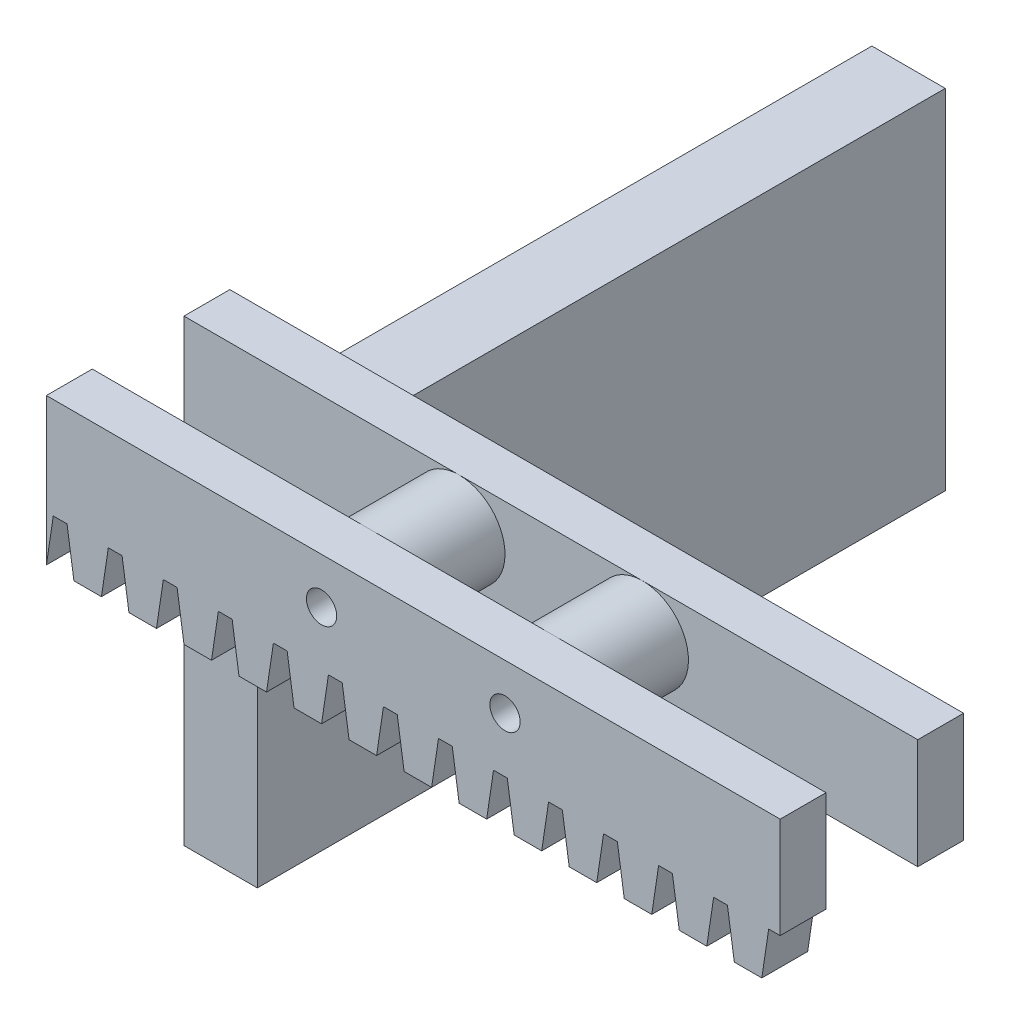
SolidWorks part; units mm, degrees
material "ABS"
ref_plane "正面" through (0, 0, 0) normal (0, 0, 1) x (1, 0, 0)
ref_plane "平面" through (0, 0, 0) normal (0, 1, 0) x (1, 0, 0)
ref_plane "右側面" through (0, 0, 0) normal (1, 0, 0) x (0, 0, -1)
sketch "ｽｹｯﾁ1" plane through (0, 0, 0) normal (0, 0, 1) x (1, 0, 0)
  line L1 (0, 0) -> (80, 0)
  line L2 (0, 0) -> (0, 16)
  line L3 (0, 16) -> (80, 16)
  line L4 (80, 0) -> (80, 16)
  dimension "D1" = 16
  dimension "D2" = 80
extrude "ﾎﾞｽ - 押し出し1" add sketch "ｽｹｯﾁ1" along normal blind 5
sketch "ｽｹｯﾁ2" plane through (0, 0, 5) normal (0, 0, 1) x (1, 0, 0)
  line L0 (0, 0) -> (0.75, 5)
  line L1 (0.75, 5) -> (2.25, 5)
  line L2 (2.25, 5) -> (3, 0)
  line L3 (0, 0) -> (80, 0) construction
  line L4 (0, 0) -> (3, 0)
  line L5 (6, 0) -> (9, 0)
  line L6 (8.25, 5) -> (9, 0)
  line L7 (6.75, 5) -> (8.25, 5)
  line L8 (6, 0) -> (6.75, 5)
  line L9 (12, 0) -> (15, 0)
  line L10 (14.25, 5) -> (15, 0)
  line L11 (12.75, 5) -> (14.25, 5)
  line L12 (12, 0) -> (12.75, 5)
  line L13 (18, 0) -> (21, 0)
  line L14 (20.25, 5) -> (21, 0)
  line L15 (18.75, 5) -> (20.25, 5)
  line L16 (18, 0) -> (18.75, 5)
  line L17 (24, 0) -> (27, 0)
  line L18 (26.25, 5) -> (27, 0)
  line L19 (24.75, 5) -> (26.25, 5)
  line L20 (24, 0) -> (24.75, 5)
  line L21 (30, 0) -> (33, 0)
  line L22 (32.25, 5) -> (33, 0)
  line L23 (30.75, 5) -> (32.25, 5)
  line L24 (30, 0) -> (30.75, 5)
  line L25 (36, 0) -> (39, 0)
  line L26 (38.25, 5) -> (39, 0)
  line L27 (36.75, 5) -> (38.25, 5)
  line L28 (36, 0) -> (36.75, 5)
  line L29 (42, 0) -> (45, 0)
  line L30 (44.25, 5) -> (45, 0)
  line L31 (42.75, 5) -> (44.25, 5)
  line L32 (42, 0) -> (42.75, 5)
  line L33 (48, 0) -> (51, 0)
  line L34 (50.25, 5) -> (51, 0)
  line L35 (48.75, 5) -> (50.25, 5)
  line L36 (48, 0) -> (48.75, 5)
  line L37 (54, 0) -> (57, 0)
  line L38 (56.25, 5) -> (57, 0)
  line L39 (54.75, 5) -> (56.25, 5)
  line L40 (54, 0) -> (54.75, 5)
  line L41 (60, 0) -> (63, 0)
  line L42 (62.25, 5) -> (63, 0)
  line L43 (60.75, 5) -> (62.25, 5)
  line L44 (60, 0) -> (60.75, 5)
  line L45 (66, 0) -> (69, 0)
  line L46 (68.25, 5) -> (69, 0)
  line L47 (66.75, 5) -> (68.25, 5)
  line L48 (66, 0) -> (66.75, 5)
  line L49 (72, 0) -> (75, 0)
  line L50 (74.25, 5) -> (75, 0)
  line L51 (72.75, 5) -> (74.25, 5)
  line L52 (72, 0) -> (72.75, 5)
  line L53 (78, 0) -> (81, 0)
  line L54 (80.25, 5) -> (81, 0)
  line L55 (78.75, 5) -> (80.25, 5)
  line L56 (78, 0) -> (78.75, 5)
  dimension "D1" = 3
  dimension "D2" = 1.5
  dimension "D3" = 5
  dimension "D4" = 14
extrude "ｶｯﾄ - 押し出し1" cut sketch "ｽｹｯﾁ2" against normal up to next
sketch "ｽｹｯﾁ3" plane through (0, 0, 5) normal (0, 0, 1) x (1, 0, 0)
  line L0 (40, 16) -> (40, 0) construction
  line L1 (80, 16) -> (0, 16) construction
  line L2 (39, 0) -> (42, 0) construction
  line L3 (50, 11) -> (30, 11) construction
  circle A0 centre (30, 11) radius 1.65
  circle A1 centre (50, 11) radius 1.65
  point P13 (40, 11)
  dimension "D3" = 3.3
  dimension "D1" = 5
  dimension "D2" = 20
extrude "ｶｯﾄ - 押し出し2" cut sketch "ｽｹｯﾁ3" against normal up to next
sketch "ｽｹｯﾁ4" plane through (0, 0, 0) normal (0, 0, -1) x (-1, 0, 0)
  circle A0 centre (-50, 11) radius 5
  circle A1 centre (-30, 11) radius 5
  circle A2 centre (-50, 11) radius 1.65
  circle A3 centre (-30, 11) radius 1.65
  circle A4 centre (-30, 11) radius 1.65 construction
  circle A5 centre (-50, 11) radius 1.65 construction
  dimension "D1" = 10
  dimension "D2" = 10
extrude "ﾎﾞｽ - 押し出し2" add sketch "ｽｹｯﾁ4" along normal blind 10 separate body
sketch "ｽｹｯﾁ5" plane through (0, 0, -10) normal (0, 0, -1) x (-1, 0, 0)
  line L1 (-80, 16) -> (0, 16)
  line L2 (-80, 16) -> (-80, 4)
  line L3 (-80, 4) -> (0, 4)
  line L4 (0, 16) -> (0, 4)
  dimension "D1" = 80
  dimension "D2" = 12
extrude "ﾎﾞｽ - 押し出し3" add sketch "ｽｹｯﾁ5" along normal blind 5
sketch "ｽｹｯﾁ6" plane through (0, 0, -15) normal (0, 0, -1) x (-1, 0, 0)
  line L1 (0, 16) -> (-8, 16)
  line L2 (0, 16) -> (0, -34)
  line L3 (0, -34) -> (-8, -34)
  line L4 (-8, 16) -> (-8, -34)
  dimension "D1" = 8
  dimension "D2" = 50
extrude "ﾎﾞｽ - 押し出し4" add sketch "ｽｹｯﾁ6" against normal blind 5
sketch "ｽｹｯﾁ7" plane through (0, 0, -15) normal (0, 0, -1) x (-1, 0, 0)
  line L0 (0, -34) -> (0, 16) construction
  line L1 (-8, -34) -> (0, -34)
  line L2 (-8, -34) -> (-8, 4)
  line L3 (-8, 4) -> (0, 4)
  line L4 (0, -34) -> (0, 4)
  line L5 (-80, 4) -> (-8, 4) construction
extrude "ﾎﾞｽ - 押し出し5" add sketch "ｽｹｯﾁ7" along normal blind 70
